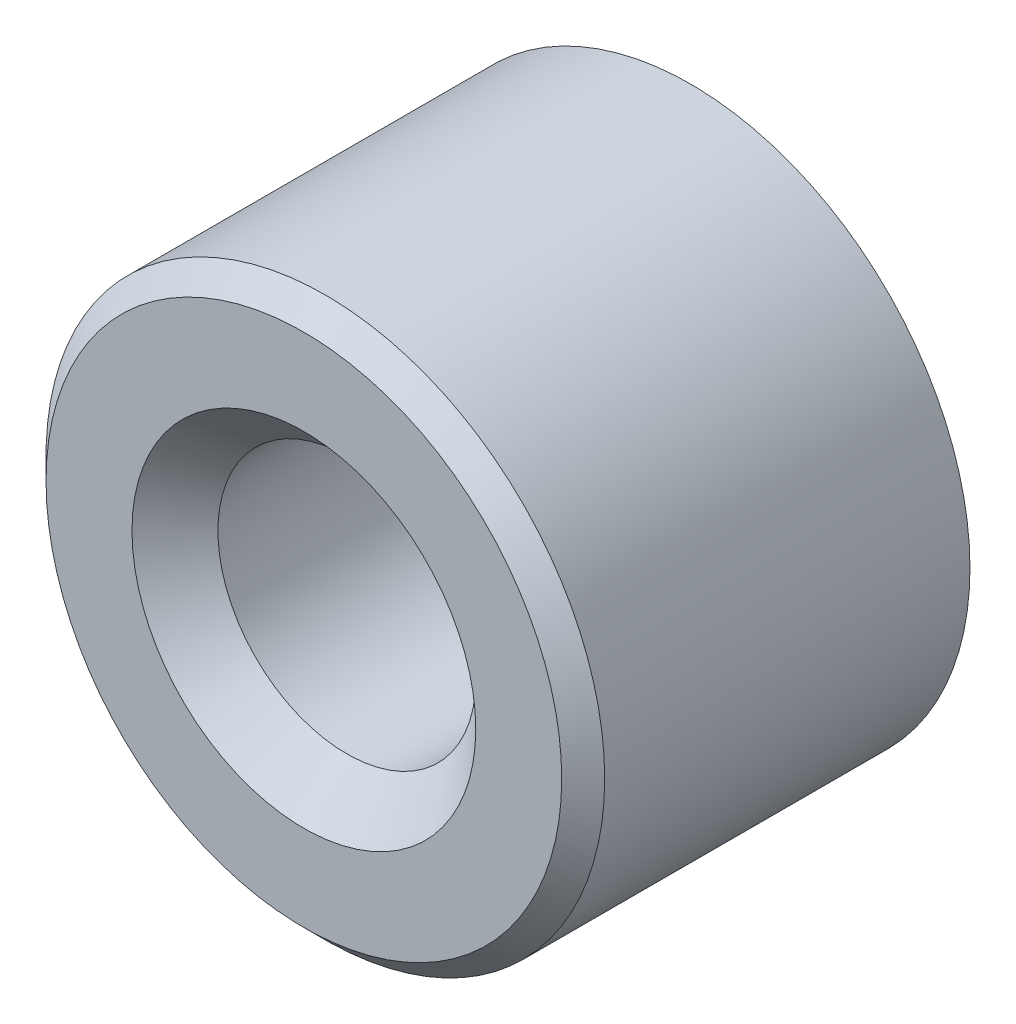
SolidWorks part; units mm, degrees
ref_plane "Спереди" through (0, 0, 0) normal (0, 0, 1) x (1, 0, 0)
ref_plane "Сверху" through (0, 0, 0) normal (0, 1, 0) x (1, 0, 0)
ref_plane "Справа" through (0, 0, 0) normal (1, 0, 0) x (0, 0, -1)
sketch "Эскиз1" plane through (0, 0, 0) normal (0, 0, 1) x (1, 0, 0)
  circle A0 centre (135, 20) radius 6.5 construction
  circle A1 centre (135, 20) radius 3 construction
  circle A2 centre (135, 20) radius 6.5
  circle A3 centre (135, 20) radius 3
extrude "Бобышка-Вытянуть1" add sketch "Эскиз1" along normal blind 2 and the other way blind 7
chamfer "Фаска1" distance 1 angle 45 1 edges at (138, 20, 2)
chamfer "Фаска2" distance 0.5 angle 45 1 edges at (141.5, 20, 2)
